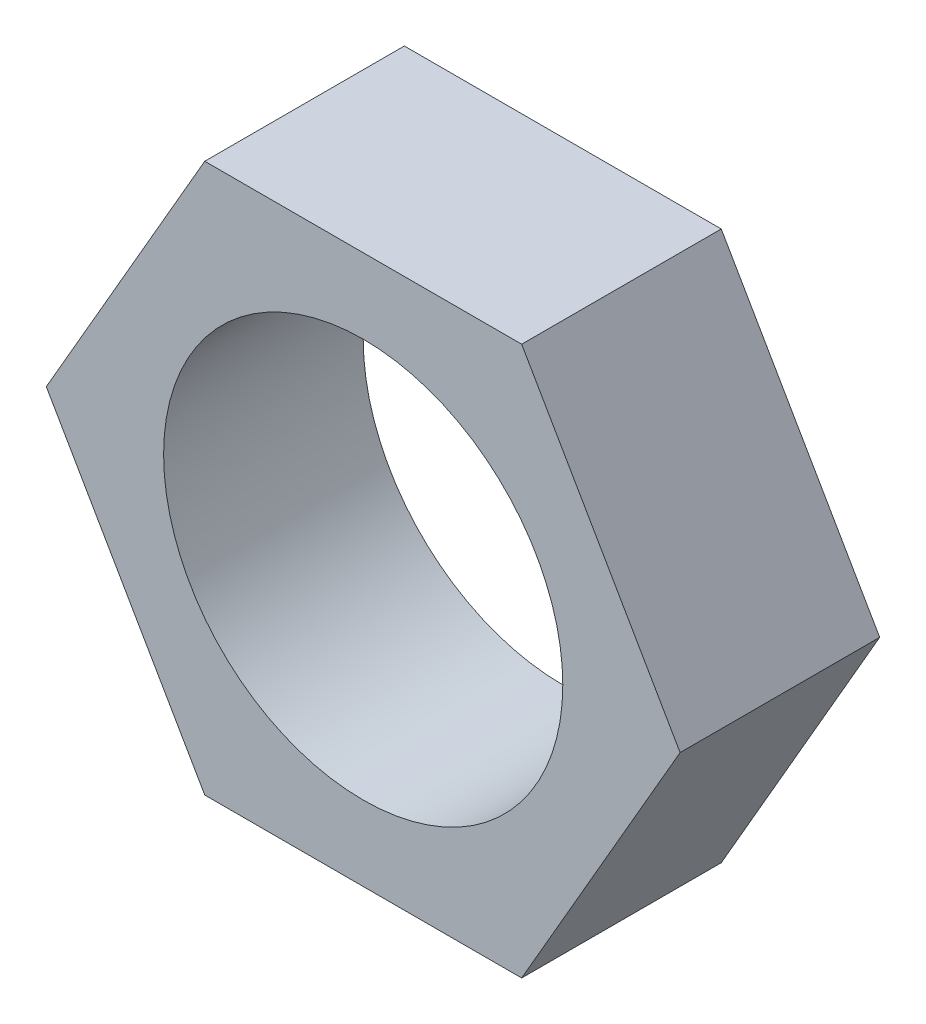
SolidWorks part; units mm, degrees
ref_plane "Front Plane" through (0, 0, 0) normal (0, 0, 1) x (1, 0, 0)
ref_plane "Top Plane" through (0, 0, 0) normal (0, 1, 0) x (1, 0, 0)
ref_plane "Right Plane" through (0, 0, 0) normal (1, 0, 0) x (0, 0, -1)
sketch "Sketch1" plane through (0, 0, 0) normal (0, 0, 1) x (1, 0, 0)
  line L1 (8.0656, 0) -> (4.0328, 6.985)
  line L2 (4.0328, 6.985) -> (-4.0328, 6.985)
  line L3 (-4.0328, 6.985) -> (-8.0656, 0)
  line L4 (-8.0656, 0) -> (-4.0328, -6.985)
  line L5 (-4.0328, -6.985) -> (4.0328, -6.985)
  line L6 (4.0328, -6.985) -> (8.0656, 0)
  circle A0 centre (0, 0) radius 6.985 construction
  dimension "D1" = 13.97
extrude "Boss-Extrude1" add sketch "Sketch1" along normal blind 5.08
sketch "Sketch2" plane through (0, 0, 5.08) normal (0, 0, 1) x (1, 0, 0)
  circle A0 centre (0, 0) radius 5.08
  dimension "D1" = 10.16
extrude "Cut-Extrude1" cut sketch "Sketch2" against normal up to next
